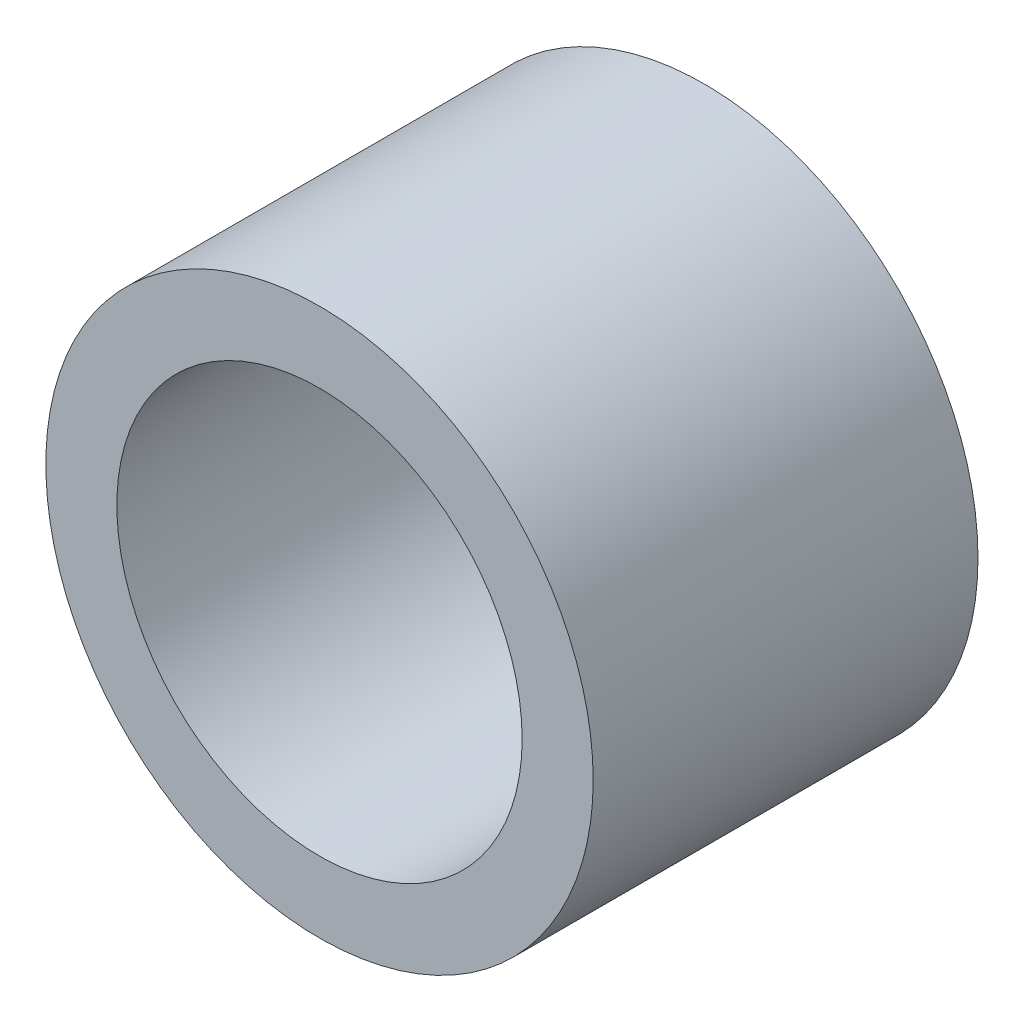
SolidWorks part; units mm, degrees
ref_plane "Front Plane" through (0, 0, 0) normal (0, 0, 1) x (1, 0, 0)
ref_plane "Top Plane" through (0, 0, 0) normal (0, 1, 0) x (1, 0, 0)
ref_plane "Right Plane" through (0, 0, 0) normal (1, 0, 0) x (0, 0, -1)
sketch "Sketch1" plane through (0, 0, 0) normal (0, 0, 1) x (1, 0, 0)
  circle A0 centre (0, 0) radius 10.668
  dimension "Pipe OD" = 21.336
extrude "Extrude-Thin1" add sketch "Sketch1" along normal mid plane 15 thin thin type one direction reverse wall 2.7686
